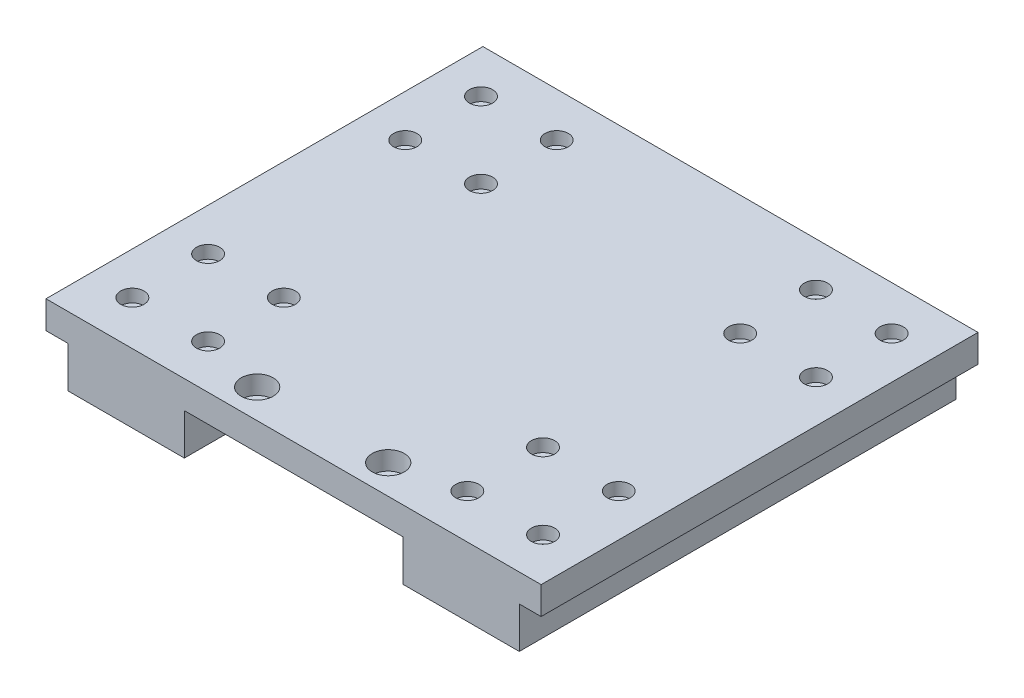
SolidWorks part; units mm, degrees
ref_plane "Plano frontal" through (0, 0, 0) normal (0, 0, 1) x (1, 0, 0)
ref_plane "Plano superior" through (0, 0, 0) normal (0, 1, 0) x (1, 0, 0)
ref_plane "Plano direito" through (0, 0, 0) normal (1, 0, 0) x (0, 0, -1)
sketch "Sketch1" plane through (0, 0, 0) normal (0, 0, 1) x (1, 0, 0)
  line L0 (-37.5, 0) -> (37.5, 0)
  line L1 (37.5, 0) -> (37.5, -14.13)
  line L2 (37.5, -14.13) -> (77.5, -14.13)
  line L3 (77.5, -14.13) -> (77.5, 0)
  line L4 (77.5, 0) -> (85, 0)
  line L5 (85, 0) -> (85, 9.5)
  line L7 (-85, 9.5) -> (-85, 0)
  line L8 (-85, 0) -> (-77.5, 0)
  line L9 (-77.5, 0) -> (-77.5, -14.13)
  line L10 (-77.5, -14.13) -> (-37.5, -14.13)
  line L11 (-37.5, -14.13) -> (-37.5, 0)
  line L12 (-85, 9.5) -> (85, 9.5)
  line L13 (0, 0) -> (0, 9.5) construction
  point P3 (0.1679, 9.5)
  point P4 (0, 0)
  point P12 (0, 0)
  dimension "D1" = 75
  dimension "D2" = 170
  dimension "D3" = 40
  dimension "D4" = 9.5
  dimension "D5" = 23.63
extrude "Boss-Extrude1" add sketch "Sketch1" along normal blind 150
hole_wizard "CBORE for M4 Hex Socket Head Cap Screw1" positions "Sketch4" profile "Sketch5" counterbore size "M4" standard "ISO" end condition through all
sketch "Sketch4" plane through (-5.2895, 9.5, 140.0466) normal (0, 1, 0) x (1, 0, 0)
  point P0 (75.7895, 31.1966)
  point P1 (49.7895, 5.1966)
  point P2 (49.7895, 31.1966)
  point P3 (75.7895, 5.1966)
sketch "Sketch5" plane through (70.5, 9.5, 108.85) normal (1, 0, 0) x (0, 0, 1)
  line L0 (0, 0) -> (0, 23.63)
  line L1 (0, 23.63) -> (2.25, 23.63)
  line L2 (2.25, 23.63) -> (2.25, 4.4)
  line L3 (2.25, 4.4) -> (4, 4.4)
  line L4 (4, 4.4) -> (4, 0)
  line L5 (4, 0) -> (0, 0)
  line L6 (0, -6.35) -> (0, 107.95) construction
  dimension "Thru Hole Dia." = 4.5
  dimension "Thru Hole Depth" = 23.63
  dimension "C'Bore Dia." = 8
  dimension "C'Bore Depth" = 4.4
mirror "Mirror2" about plane through (0, 0, 0) normal (1, 0, 0) of "CBORE for M4 Hex Socket Head Cap Screw1"
ref_plane "Plane1" through (0, 0, 75) normal (0, 0, 1) x (1, 0, 0)
mirror "Mirror3" about plane through (0, 0, 75) normal (0, 0, 1) of "Mirror2", "CBORE for M4 Hex Socket Head Cap Screw1"
hole_wizard "CBORE for M6 Hex Socket Head Cap Screw1" positions "Sketch6" profile "Sketch7" counterbore size "M6" standard "ISO"
sketch "Sketch6" plane through (-5.2895, 9.5, 140.0466) normal (0, 1, 0) x (1, 0, 0)
  point P0 (27.7895, 0.0466)
  point P1 (-17.2105, 0.0466)
sketch "Sketch7" plane through (22.5, 9.5, 140) normal (1, 0, 0) x (0, 0, 1)
  line L0 (0, 0) -> (0, 23.63)
  line L1 (0, 23.63) -> (3.3, 23.63)
  line L2 (3.3, 23.63) -> (3.3, 6.4)
  line L3 (3.3, 6.4) -> (5.5, 6.4)
  line L4 (5.5, 6.4) -> (5.5, 0)
  line L5 (5.5, 0) -> (0, 0)
  line L6 (0, -6.35) -> (0, 107.95) construction
  dimension "Thru Hole Dia." = 6.6
  dimension "Thru Hole Depth" = 23.63
  dimension "C'Bore Dia." = 11
  dimension "C'Bore Depth" = 6.4
